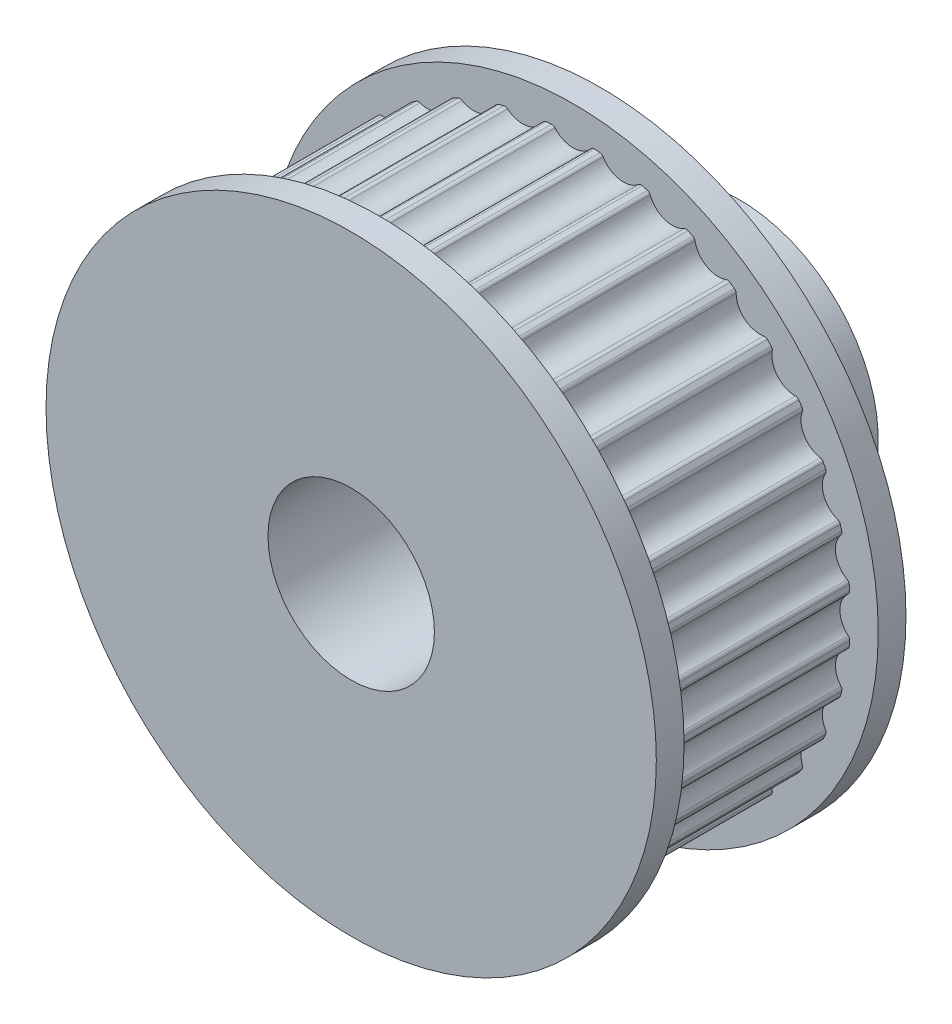
SolidWorks part; units mm, degrees
ref_plane "Ön Düzlem" through (0, 0, 0) normal (0, 0, 1) x (1, 0, 0)
ref_plane "Üst Düzlem" through (0, 0, 0) normal (0, 1, 0) x (1, 0, 0)
ref_plane "Sağ Düzlem" through (0, 0, 0) normal (1, 0, 0) x (0, 0, -1)
sketch "Çizim1" plane through (0, 0, 0) normal (0, 0, 1) x (1, 0, 0)
  circle A0 centre (0, 0) radius 10
  circle A1 centre (0, 0) radius 3
  dimension "D1" = 6
  dimension "D2" = 20
extrude "Yükseklik-Ekstrüzyon1" add sketch "Çizim1" along normal blind 7
sketch "Çizim2" plane through (0, 0, 7) normal (0, 0, 1) x (1, 0, 0)
  arc A3 (-0.6943, 9.9759) -> (0.6943, 9.9759) centre (0, 10.4681) ccw
  arc A4 (0.6943, 9.9759) -> (-0.6943, 9.9759) centre (0, 0) ccw
  circle A5 centre (0, 0) radius 10 construction
extrude "Kes-Ekstrüzyon2" cut sketch "Çizim2" against normal blind 7 contours A3 A4
fillet "Radyus2" radius 0.15 2 edges at (0.6943, 9.9759, 3.5) (-0.6943, 9.9759, 3.5)
pattern_circular "Dairesel Kaplama2" count 36 over 360 about axis through (0, 0, 0) along (0, 0, 1) of "Kes-Ekstrüzyon2", "Radyus2"
sketch "Çizim4" plane through (0, 0, 7) normal (0, 0, 1) x (1, 0, 0)
  circle A0 centre (0, 0) radius 3
  circle A1 centre (0, 0) radius 11
  dimension "D1" = 6
  dimension "D2" = 22
extrude "Yükseklik-Ekstrüzyon2" add sketch "Çizim4" along normal blind 1
sketch "Çizim5" plane through (0, 0, 0) normal (0, 0, -1) x (-1, 0, 0)
  circle A1 centre (0, 0) radius 11
  dimension "D2" = 22
extrude "Yükseklik-Ekstrüzyon4" add sketch "Çizim5" along normal blind 1
ref_plane "Düzlem1" through (0, 10, 0) normal (0, 1, 0) x (1, 0, 0)
sketch "草圖1" plane through (0, 0, -1) normal (0, 0, -1) x (-1, 0, 0)
  circle A0 centre (0, 0) radius 5
  circle A1 centre (0, 0) radius 3
  dimension "D1" = 10
  dimension "D2" = 6
extrude "填料-伸長1" add sketch "草圖1" along normal blind 5
sketch "Çizim6" plane through (0, 10, 0) normal (0, 1, 0) x (1, 0, 0)
  line L1 (3, 6) -> (-3, 6) construction
  circle A0 centre (0, 3.5) radius 1.5
  dimension "D1" = 2.5
  dimension "D2" = 3
sketch "草圖2" plane through (0, 0, -1) normal (0, 0, -1) x (-1, 0, 0)
  circle A0 centre (0, 0) radius 3
extrude "除料-伸長1" cut sketch "草圖2" against normal blind 5
extrude "除料-伸長2" cut sketch "Çizim6" against normal up to surface (7 mm away)
ref_plane "平面1" through (10, 0, 0) normal (1, 0, 0) x (0, 0, -1)
sketch "草圖3" plane through (10, 0, 0) normal (1, 0, 0) x (0, 0, -1)
  line L0 (6, -5) -> (6, 5) construction
  circle A0 centre (3.5, 0) radius 1.5
  dimension "D1" = 3
  dimension "D2" = 2.5
extrude "除料-伸長3" cut sketch "草圖3" against normal up to next
